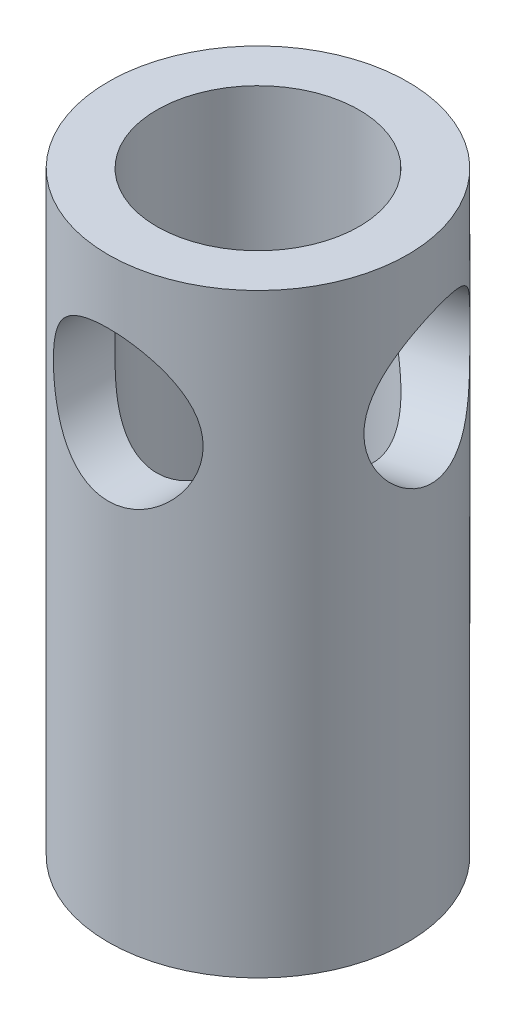
SolidWorks part; units mm, degrees
ref_plane "Front Plane" through (0, 0, 0) normal (0, 0, 1) x (1, 0, 0)
ref_plane "Top Plane" through (0, 0, 0) normal (0, 1, 0) x (1, 0, 0)
ref_plane "Right Plane" through (0, 0, 0) normal (1, 0, 0) x (0, 0, -1)
sketch "Sketch1" plane through (0, 0, 0) normal (0, 1, 0) x (1, 0, 0)
  circle A0 centre (0, 0) radius 4
  circle A1 centre (0, 0) radius 2.7
  dimension "D1" = 8
  dimension "D2" = 5.4
extrude "Boss-Extrude1" add sketch "Sketch1" along normal mid plane 15.9
sketch "Sketch2" plane through (0, 0, 0) normal (0, 0, 1) x (1, 0, 0)
  line L0 (4, 7.95) -> (-4, 7.95) construction
  circle A0 centre (0, 4.25) radius 2
  dimension "D1" = 4
  dimension "D2" = 3.7
extrude "Cut-Extrude1" cut sketch "Sketch2" along normal through all
pattern_circular "CirPattern1" count 2 every 105 about axis through (0, 7.95, 0) along (0, -1, 0) of "Cut-Extrude1"
